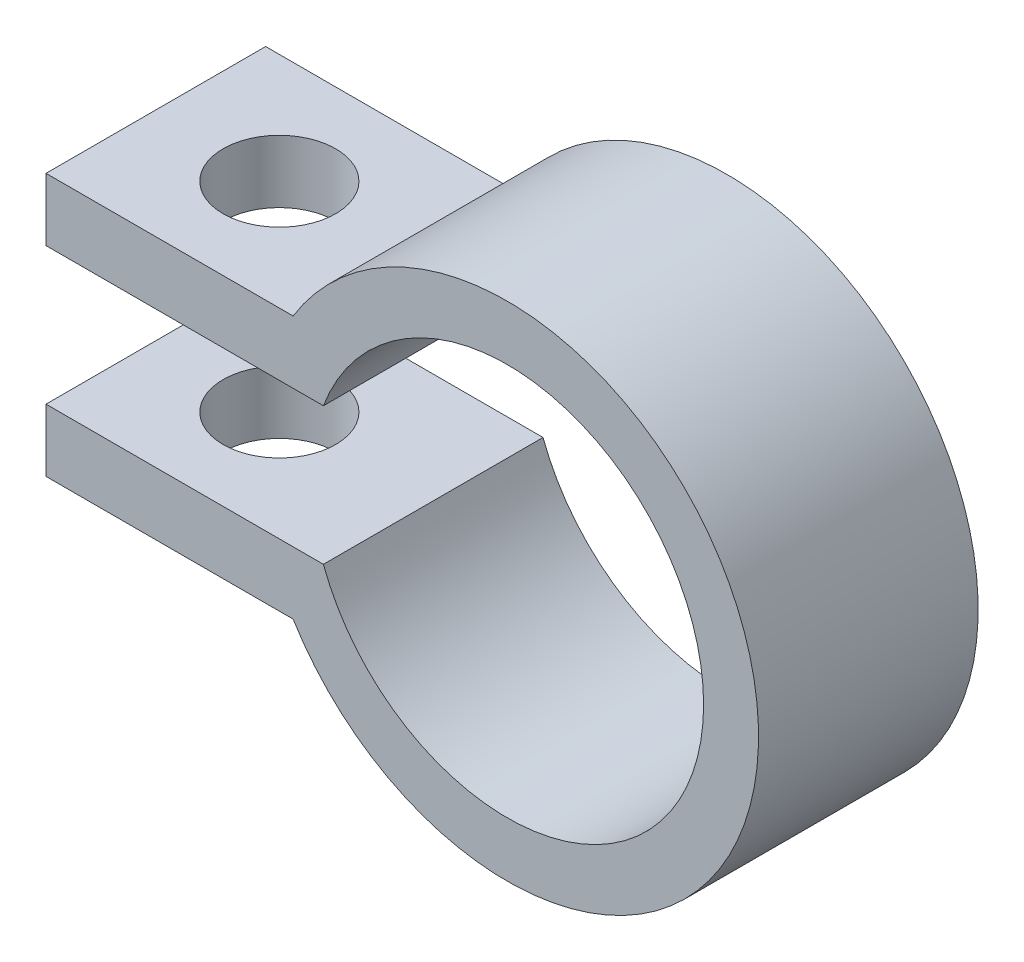
SolidWorks part; units mm, degrees
material "PLA"
ref_plane "Front Plane" through (0, 0, 0) normal (0, 0, 1) x (1, 0, 0)
ref_plane "Top Plane" through (0, 0, 0) normal (0, 1, 0) x (1, 0, 0)
ref_plane "Right Plane" through (0, 0, 0) normal (1, 0, 0) x (0, 0, -1)
sketch "Sketch1" plane through (0, 0, 0) normal (0, 0, 1) x (1, 0, 0)
  line L0 (-8.8018, 2.5) -> (-6.6987, 2.5)
  line L1 (-16.8018, -2.5) -> (-8.8018, -2.5)
  line L3 (-16.8018, 2.5) -> (-8.8018, 2.5)
  line L5 (-16.8018, -2.5) -> (-8.8018, 2.5) construction
  line L6 (-16.8018, 2.5) -> (-8.8018, -2.5) construction
  line L7 (-16.8018, 2.5) -> (-8.8018, 2.5)
  line L8 (-16.8018, 2.5) -> (-16.8018, 4.7806)
  line L9 (-16.8018, 4.7806) -> (-7.8018, 4.7806)
  line L11 (-16.8018, -2.5) -> (-8.8018, -2.5)
  line L12 (-16.8018, -2.5) -> (-16.8018, -4.7806)
  line L13 (-16.8018, -4.7806) -> (-7.8018, -4.7806)
  line L15 (-8.8018, -2.5) -> (-6.6987, -2.5)
  arc A0 (-6.6987, -2.5) -> (-6.6987, 2.5) centre (0, 0) ccw
  arc A1 (-7.8018, -4.7806) -> (-7.8018, 4.7806) centre (0, 0) ccw
  point P4 (-12.8018, 0)
  dimension "D1" = 2
  dimension "D2" = 14.3
  dimension "D3" = 8
  dimension "D4" = 5
  dimension "D5" = 9
extrude "Boss-Extrude1" add sketch "Sketch1" along normal blind 8 contours L13 A1 L9 L8 L3 L0 A0 L15 L1 L12
sketch "Sketch3" plane through (0, 4.7806, 0) normal (0, 1, 0) x (1, 0, 0)
  line L0 (-12.3018, 0) -> (-12.3018, -8) construction
  line L1 (-16.8018, 0) -> (-7.8018, 0) construction
  line L2 (-16.8018, -8) -> (-7.8018, -8) construction
  circle A0 centre (-12.3018, -4) radius 2.05
  point P2 (-12.3018, -3.25)
  dimension "D1" = 4.1
extrude "Cut-Extrude1" cut sketch "Sketch3" against normal blind 18.5
